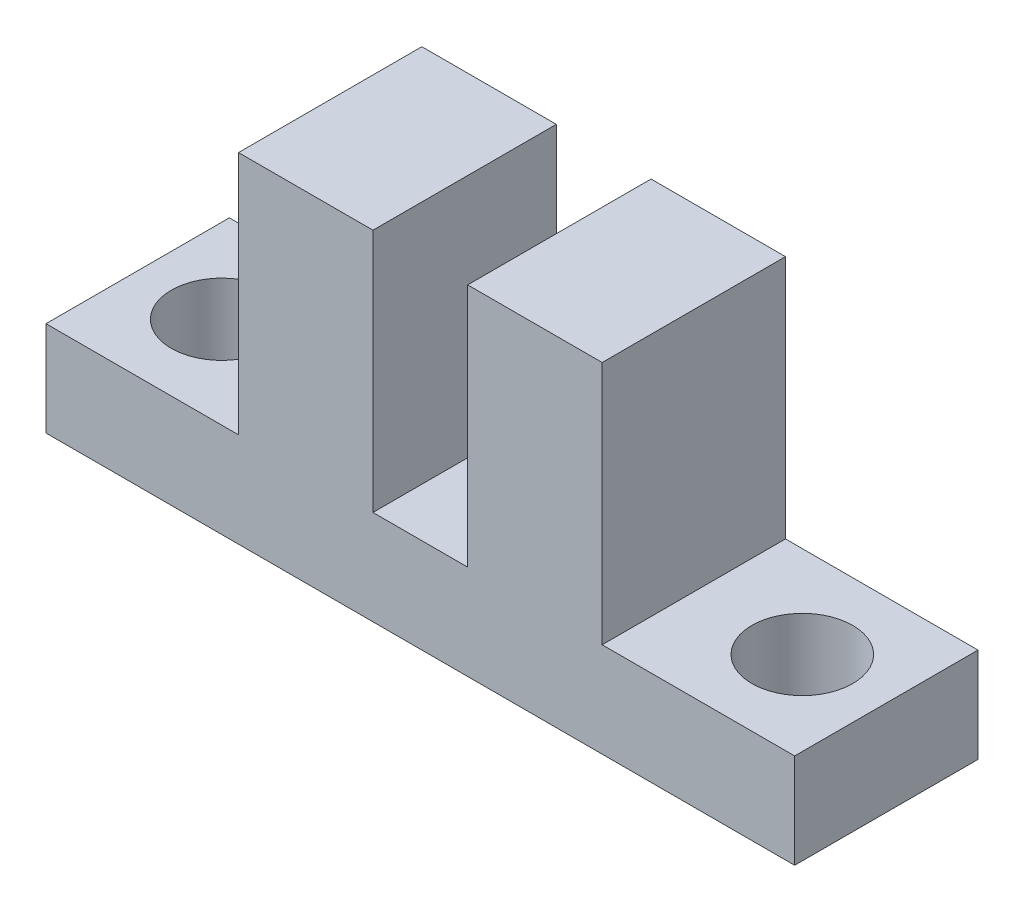
SolidWorks part; units mm, degrees
ref_plane "Front Plane" through (0, 0, 0) normal (0, 0, 1) x (1, 0, 0)
ref_plane "Top Plane" through (0, 0, 0) normal (0, 1, 0) x (1, 0, 0)
ref_plane "Right Plane" through (0, 0, 0) normal (1, 0, 0) x (0, 0, -1)
sketch "Sketch1" plane through (0, 0, 0) normal (0, 1, 0) x (1, 0, 0)
  line L0 (0, 3) -> (24.5, 3) construction
  line L1 (0, 0) -> (24.5, 0)
  line L2 (0, 0) -> (0, 6)
  line L3 (0, 6) -> (24.5, 6)
  line L4 (24.5, 0) -> (24.5, 6)
  circle A0 centre (2.75, 3) radius 1.65
  circle A1 centre (21.75, 3) radius 1.65
  dimension "D3" = 3.3
  dimension "D4" = 3.3
  dimension "D1" = 24.5
  dimension "D2" = 6
  dimension "D5" = 2.75
  dimension "D6" = 19
extrude "Boss-Extrude1" add sketch "Sketch1" along normal blind 3.1
sketch "Sketch2" plane through (0, 3.1, 0) normal (0, 1, 0) x (1, 0, 0)
  line L0 (24.5, 6) -> (0, 6) construction
  line L1 (6.3, 6) -> (10.7, 6)
  line L2 (6.3, 6) -> (6.3, 0)
  line L3 (6.3, 0) -> (10.7, 0)
  line L4 (10.7, 6) -> (10.7, 0)
  line L5 (0, 0) -> (24.5, 0) construction
  line L6 (0, 6) -> (0, 0) construction
  line L7 (13.8, 6) -> (18.2, 6)
  line L8 (13.8, 6) -> (13.8, 0)
  line L9 (13.8, 0) -> (18.2, 0)
  line L10 (18.2, 6) -> (18.2, 0)
  dimension "D1" = 6.3
  dimension "D2" = 3.1
  dimension "D3" = 4.4
  dimension "D4" = 4.4
extrude "Boss-Extrude2" add sketch "Sketch2" along normal blind 8
